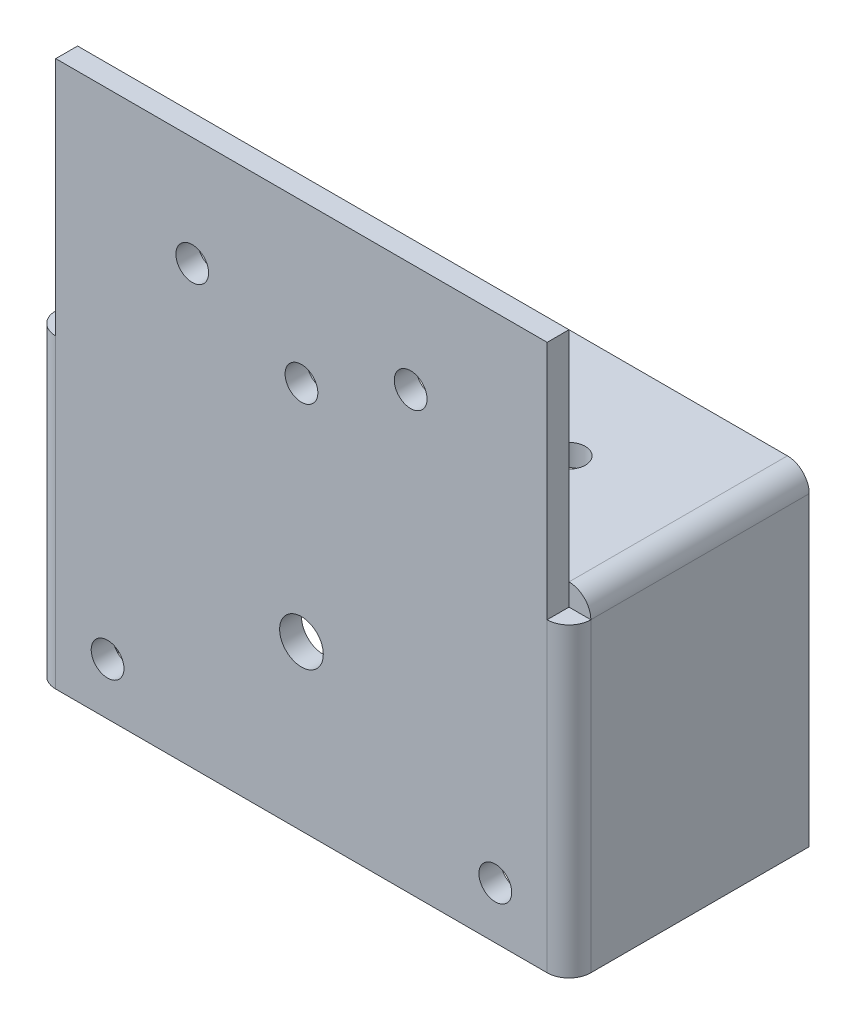
SolidWorks part; units mm, degrees
ref_plane "Front Plane" through (0, 0, 0) normal (0, 0, 1) x (1, 0, 0)
ref_plane "Top Plane" through (0, 0, 0) normal (0, 1, 0) x (1, 0, 0)
ref_plane "Right Plane" through (0, 0, 0) normal (1, 0, 0) x (0, 0, -1)
sketch "Sketch1" plane through (0, 0, 0) normal (0, 0, 1) x (1, 0, 0)
  line L1 (-24.5, -25) -> (24.5, -25)
  line L2 (-24.5, -25) -> (-24.5, 25)
  line L3 (-24.5, 25) -> (24.5, 25)
  line L4 (24.5, -25) -> (24.5, 25)
  line L5 (-24.5, -25) -> (24.5, 25) construction
  line L6 (-24.5, 25) -> (24.5, -25) construction
  point P0 (0, 0)
  dimension "D1" = 50
  dimension "D2" = 49
extrude "Boss-Extrude1" add sketch "Sketch1" along normal blind 2
sketch "Sketch3" plane through (0, 0, 2) normal (0, 0, 1) x (1, 0, 0)
  line L0 (-22.5, 25) -> (-22.5, 3)
  line L1 (24.5, 25) -> (-24.5, 25) construction
  line L2 (-22.5, 3) -> (-24.5, 3)
  line L3 (-24.5, 25) -> (-24.5, -25) construction
  line L4 (0, 0) -> (0, 19.4697) construction
  line L5 (-24.5, 3) -> (-24.5, 25)
  line L6 (-24.5, 25) -> (-22.5, 25)
  line L7 (24.5, 25) -> (22.5, 25)
  line L8 (24.5, 3) -> (24.5, 25)
  line L9 (22.5, 3) -> (24.5, 3)
  line L10 (22.5, 25) -> (22.5, 3)
  dimension "D1" = 2
  dimension "D2" = 22
extrude "Cut-Extrude1" cut sketch "Sketch3" against normal through all
sketch "Sketch7" plane through (0, 0, 0) normal (0, 0, -1) x (-1, 0, 0)
  line L0 (-24.5, -25) -> (-24.5, 5)
  line L2 (-22.49, 3) -> (-22.49, -25)
  line L3 (24.5, -25) -> (-24.5, -25) construction
  line L4 (-22.49, -25) -> (-24.5, -25)
  line L7 (-2.49, 5) -> (-2.49, 3)
  line L8 (-2.49, 3) -> (-22.49, 3)
  line L9 (-24.5, 5) -> (-2.49, 5)
  line L10 (-22.5, 25) -> (22.5, 25) construction
  line L11 (0, 0) -> (0, 21.2442) construction
  line L12 (24.5, 5) -> (2.49, 5)
  line L13 (2.49, 3) -> (22.49, 3)
  line L14 (2.49, 5) -> (2.49, 3)
  line L15 (22.49, -25) -> (24.5, -25)
  line L16 (22.49, 3) -> (22.49, -25)
  line L17 (24.5, -25) -> (24.5, 5)
  dimension "D1" = 20
  dimension "D2" = 2
  dimension "D3" = 2.01
  dimension "D4" = 20
extrude "Boss-Extrude5" add sketch "Sketch7" along normal blind 20
fillet "Fillet3" radius 2 4 edges at (-24.5, 5, -10) (24.5, 5, -10) (-24.5, -11, 2) (24.5, -11, 2)
fillet "Fillet4" radius 1 4 edges at (22.49, 3, -10) (22.49, -11, 0) (-22.49, -11, 0) (-22.49, 3, -10)
sketch "Sketch8" plane through (0, 0, 2) normal (0, 0, 1) x (1, 0, 0)
  line L0 (0, 0) -> (0, -10) construction
  line L1 (-22.5, 15) -> (22.5, 15) construction
  line L2 (-22.5, 3) -> (-22.5, 25) construction
  line L3 (22.5, 25) -> (22.5, 3) construction
  line L4 (22.5, 25) -> (-22.5, 25) construction
  line L5 (-22.5, -25) -> (22.5, -25) construction
  circle A0 centre (0, -10) radius 2
  circle A1 centre (0, 10.5) radius 1.5
  circle A2 centre (17.7535, -20.25) radius 1.5
  circle A3 centre (-17.7535, -20.25) radius 1.5
  circle A4 centre (-10, 15) radius 1.5
  circle A6 centre (10, 15) radius 1.5
  point P12 (0, -10)
  dimension "D1" = 4
  dimension "D2" = 3
  dimension "D3" = 20.5
  dimension "D6" = 3
  dimension "D7" = 20
  dimension "D8" = 15
  dimension "D5" = 10
  dimension "D4" = 3
extrude "Cut-Extrude2" cut sketch "Sketch8" against normal blind 10
sketch "Sketch9" plane through (0, 5, 0) normal (0, 1, 0) x (1, 0, 0)
  line L0 (22.5, 10) -> (-22.5, 10) construction
  line L1 (22.5, 0) -> (22.5, 20) construction
  line L2 (-22.5, 20) -> (-22.5, 0) construction
  line L3 (0, 0) -> (0, 22.7242) construction
  line L4 (12.495, 20) -> (12.495, 0) construction
  line L5 (2.49, 20) -> (22.5, 20) construction
  line L6 (2.49, 0) -> (22.5, 0) construction
  circle A0 centre (12.495, 10) radius 1.5
  circle A1 centre (-12.495, 10) radius 1.5
  point P19 (0, 0)
  dimension "D1" = 3
extrude "Cut-Extrude3" cut sketch "Sketch9" against normal through all both and the other way through all
